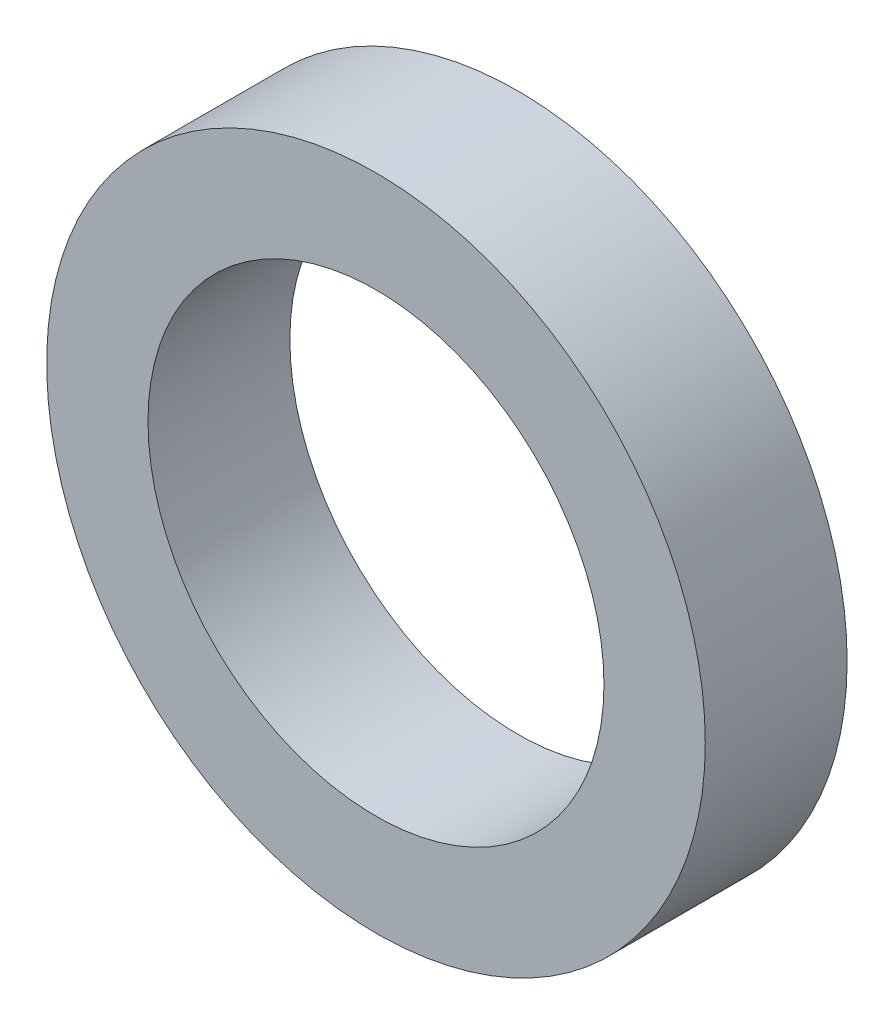
SolidWorks part; units mm, degrees
ref_plane "前视基准面" through (0, 0, 0) normal (0, 0, 1) x (1, 0, 0)
ref_plane "上视基准面" through (0, 0, 0) normal (0, 1, 0) x (1, 0, 0)
ref_plane "右视基准面" through (0, 0, 0) normal (1, 0, 0) x (0, 0, -1)
sketch "草图1" plane through (0, 0, 0) normal (0, 0, 1) x (1, 0, 0)
  circle A0 centre (0, 0) radius 32.5
  circle A1 centre (0, 0) radius 22.5
  dimension "D1" = 45
  dimension "D2" = 65
extrude "凸台-拉伸1" add sketch "草图1" along normal blind 14
